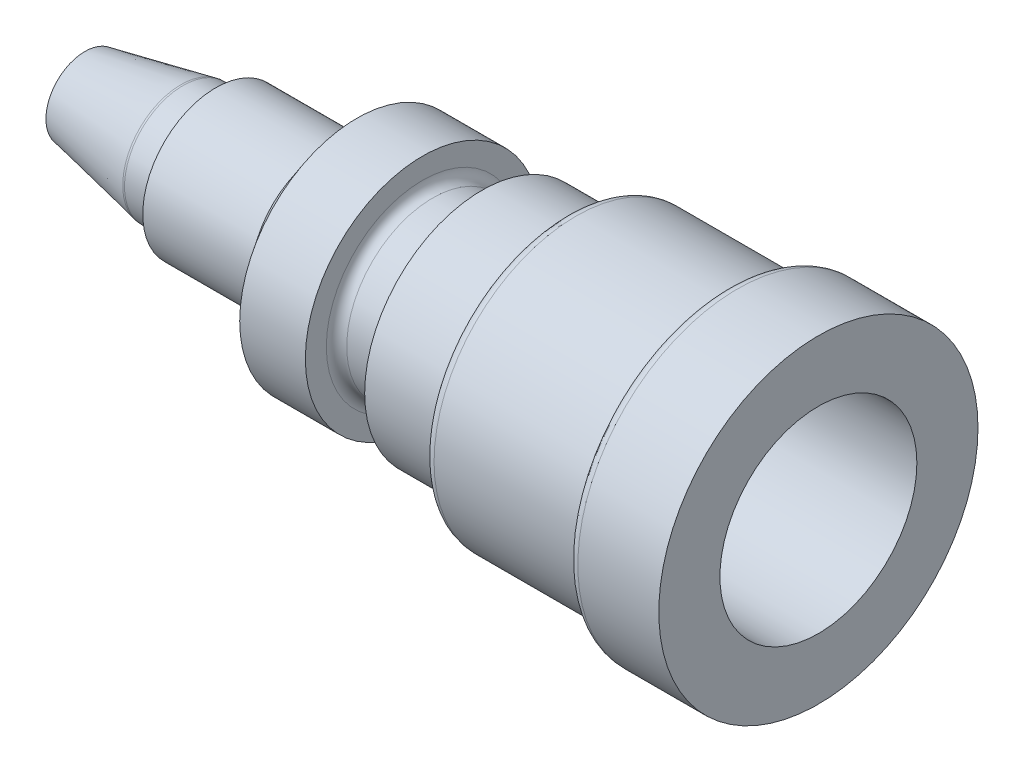
SolidWorks part; units mm, degrees
ref_plane "Front Plane" through (0, 0, 0) normal (0, 0, 1) x (1, 0, 0)
ref_plane "Top Plane" through (0, 0, 0) normal (0, 1, 0) x (1, 0, 0)
ref_plane "Right Plane" through (0, 0, 0) normal (1, 0, 0) x (0, 0, -1)
sketch "Sketch3" plane through (0, 0, 0) normal (0, 1, 0) x (1, 0, 0)
  line L0 (-13.0082, 5.461) -> (-4.9088, 5.461)
  line L1 (-4.9088, 5.461) -> (-2.4544, 8.763)
  line L2 (-2.4544, 8.763) -> (2.4544, 8.763)
  line L3 (2.4544, 8.763) -> (2.4544, 7.1933)
  line L4 (3.2164, 6.4313) -> (6.1299, 6.4313)
  line L5 (6.8919, 7.1933) -> (6.8919, 8.763)
  line L6 (6.8919, 8.763) -> (13.1823, 8.763)
  line L7 (13.1823, 8.763) -> (13.1823, 9.8616)
  line L8 (13.9443, 10.6236) -> (25.2492, 10.6236)
  line L9 (25.2492, 10.6236) -> (25.2492, 11.176)
  line L10 (26.0112, 11.938) -> (32.0677, 11.938)
  line L11 (32.0677, 11.938) -> (32.0677, 0)
  line L12 (32.0677, 0) -> (-13.0082, 0)
  line L13 (-13.0082, 0) -> (-22.7963, 0)
  line L14 (-22.7963, 0) -> (-22.7963, 2.9158)
  line L15 (-22.7963, 2.9158) -> (-15.6129, 4.3572)
  line L16 (-15.463, 4.3721) -> (-13.0082, 4.3721)
  line L17 (-13.0082, 4.3721) -> (-13.0082, 5.461)
  arc A0 (6.1299, 6.4313) -> (6.8919, 7.1933) centre (6.1299, 7.1933) ccw
  arc A1 (2.4544, 7.1933) -> (3.2164, 6.4313) centre (3.2164, 7.1933) ccw
  arc A2 (13.1823, 9.8616) -> (13.9443, 10.6236) centre (13.9443, 9.8616) cw
  arc A3 (25.2492, 11.176) -> (26.0112, 11.938) centre (26.0112, 11.176) cw
  arc A4 (-15.6129, 4.3572) -> (-15.463, 4.3721) centre (-15.463, 3.6101) cw
  dimension "D5" = 0.762
  dimension "D6" = 0.762
  dimension "D1" = 5.461
  dimension "D2" = 8.763
  dimension "D3" = 54.864
  dimension "D4" = 11.938
revolve "Revolve1" add sketch "Sketch3" angle 360 about L12
sketch "Sketch4" plane through (32.0677, 0, 0) normal (1, 0, 0) x (0, 0, -1)
  circle A0 centre (0, 0) radius 7.366
  dimension "D1" = 14.732
extrude "Cut-Extrude1" cut sketch "Sketch4" against normal blind 12.7
sketch "Sketch5" plane through (-22.7963, 0, 0) normal (-1, 0, 0) x (0, 0, 1)
  circle A0 centre (0, 0) radius 1.2853
extrude "Cut-Extrude2" cut sketch "Sketch5" against normal through all
